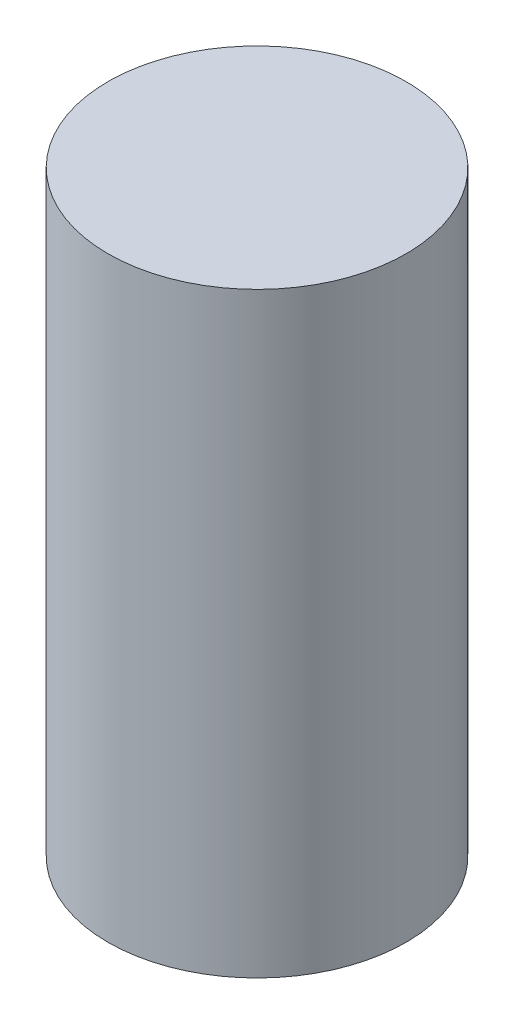
SolidWorks part; units mm, degrees
material "Alloy Steel"
ref_plane "Front Plane" through (0, 0, 0) normal (0, 0, 1) x (1, 0, 0)
ref_plane "Top Plane" through (0, 0, 0) normal (0, 1, 0) x (1, 0, 0)
ref_plane "Right Plane" through (0, 0, 0) normal (1, 0, 0) x (0, 0, -1)
sketch "Sketch2" plane through (0, 0, 0) normal (0, 1, 0) x (1, 0, 0)
  circle A0 centre (0, 0) radius 6.35
  dimension "D1" = 12.7
extrude "Boss-Extrude1" add sketch "Sketch2" along normal blind 25.4
